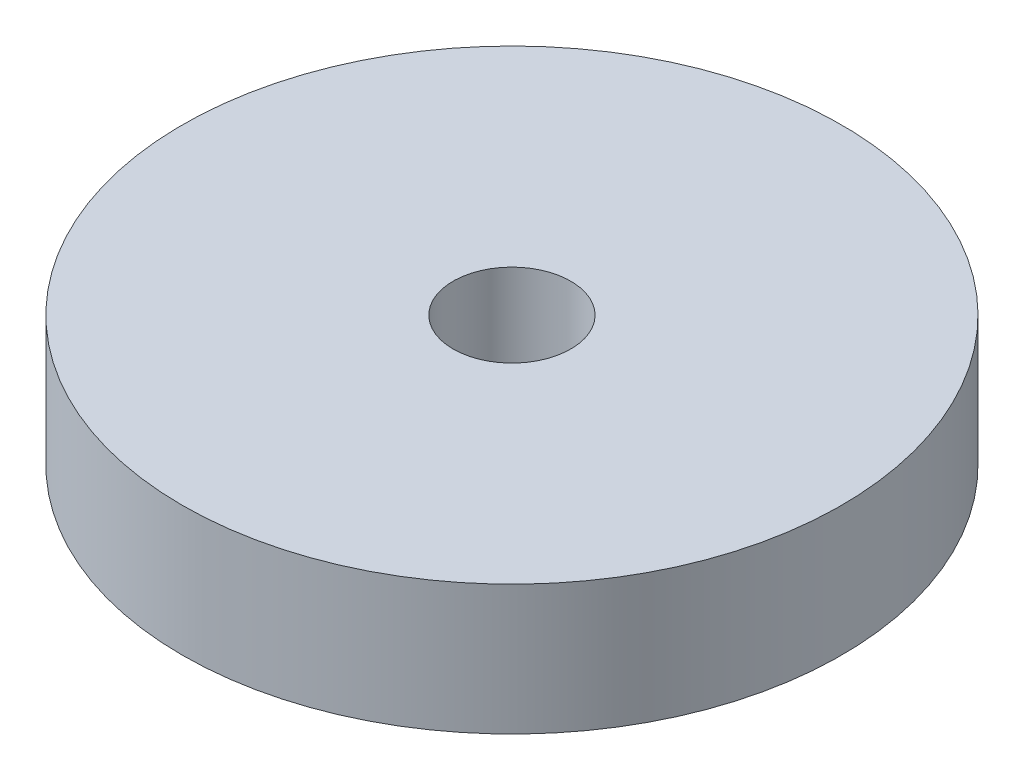
SolidWorks part; units mm, degrees
ref_plane "Front Plane" through (0, 0, 0) normal (0, 0, 1) x (1, 0, 0)
ref_plane "Top Plane" through (0, 0, 0) normal (0, 1, 0) x (1, 0, 0)
ref_plane "Right Plane" through (0, 0, 0) normal (1, 0, 0) x (0, 0, -1)
sketch "Sketch1" plane through (0, 0, 0) normal (0, 1, 0) x (1, 0, 0)
  circle A0 centre (0, 0) radius 162.5
  circle A1 centre (0, 0) radius 29
  dimension "D1" = 325
  dimension "D2" = 58
extrude "Boss-Extrude1" add sketch "Sketch1" along normal mid plane 64
